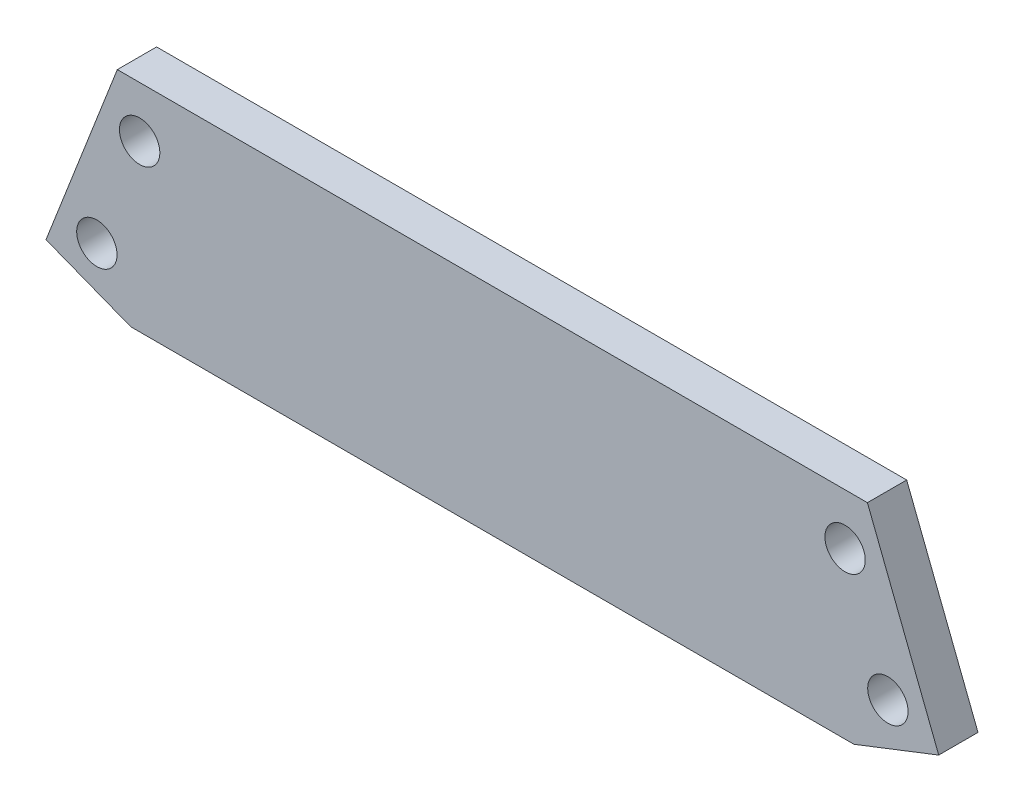
SolidWorks part; units mm, degrees
ref_plane "Front Plane" through (0, 0, 0) normal (0, 0, 1) x (1, 0, 0)
ref_plane "Top Plane" through (0, 0, 0) normal (0, 1, 0) x (1, 0, 0)
ref_plane "Right Plane" through (0, 0, 0) normal (1, 0, 0) x (0, 0, -1)
sketch "Sketch1" plane through (0, 0, -140.4937) normal (0, 0, -1) x (-1, 0, 0)
  line L0 (-60.6432, 1084.0887) -> (60.6432, 1084.0887)
  line L1 (-54.7268, 1081.7824) -> (-65.0805, 1085.8183) construction
  line L2 (54.7268, 1081.7824) -> (65.0805, 1085.8183) construction
  line L3 (60.6432, 1084.0887) -> (72.1742, 1054.5066)
  line L4 (76.6115, 1056.2363) -> (66.2578, 1052.2004) construction
  line L6 (-76.6115, 1056.2363) -> (-66.2578, 1052.2004) construction
  line L7 (-72.1742, 1054.5066) -> (-60.6432, 1084.0887)
  line L8 (-65.0805, 1085.8183) -> (-76.6115, 1056.2363) construction
  line L9 (65.0805, 1085.8183) -> (76.6115, 1056.2363) construction
  line L10 (72.1742, 1054.5066) -> (58.4673, 1049.1637)
  line L11 (58.4673, 1049.1637) -> (-58.4673, 1049.1637)
  line L12 (-58.4673, 1049.1637) -> (-72.1742, 1054.5066)
  circle A0 centre (-57.033, 1075.866) radius 3.2639 construction
  circle A1 centre (-57.033, 1075.866) radius 3.2639
  circle A2 centre (-63.9516, 1058.1168) radius 3.2639 construction
  circle A3 centre (-63.9516, 1058.1168) radius 3.2639
  circle A4 centre (57.033, 1075.866) radius 3.2639 construction
  circle A5 centre (57.033, 1075.866) radius 3.2639
  circle A6 centre (63.9516, 1058.1168) radius 3.2639 construction
  circle A7 centre (63.9516, 1058.1168) radius 3.2639
  dimension "D1" = 4.7625
  dimension "D2" = 34.925
extrude "Boss-Extrude1" add sketch "Sketch1" along normal blind 6.35
